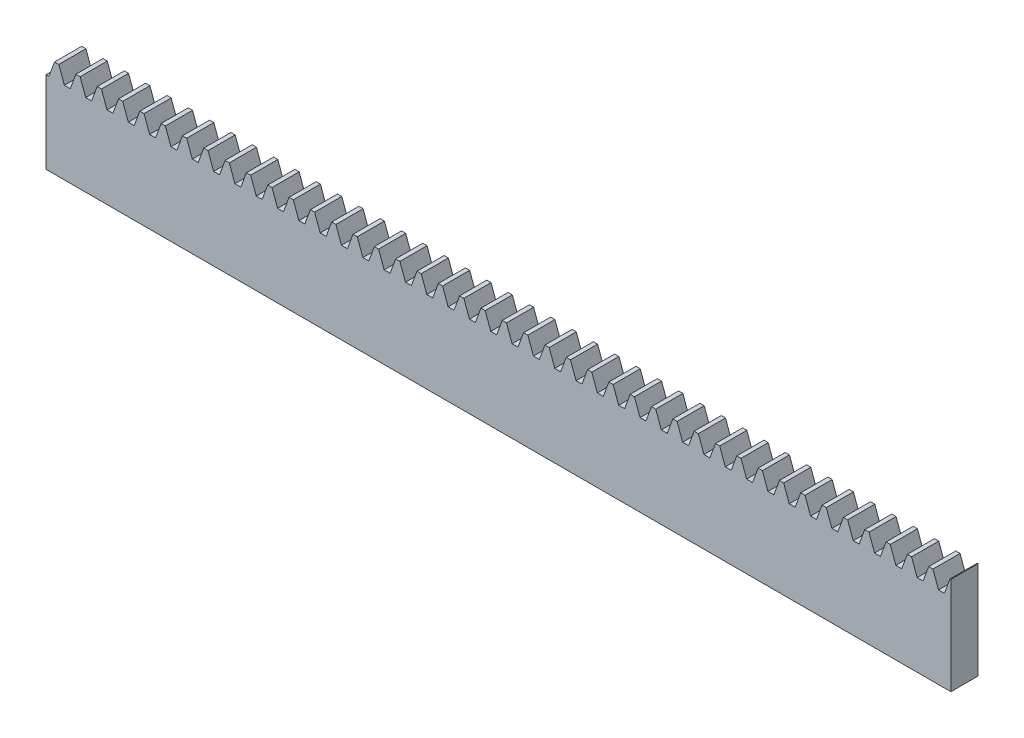
SolidWorks part; units mm, degrees
extrude "Blank" add sketch "BlankSke" against normal blind 12
sketch "BlankSke" plane through (0, 0, 0) normal (0, 0, 1) x (1, 0, 0)
  line L1 (0, 0) -> (400, 0)
  line L2 (0, 0) -> (0, 43)
  line L3 (0, 43) -> (400, 43)
  line L4 (400, 0) -> (400, 43)
  dimension "Length" = 400
  dimension "Blank_height" = 43
ref_plane "Plane1" through (0, 0, 0) normal (0, 0, 1) x (1, 0, 0)
ref_plane "Plane2" through (0, 0, 0) normal (0, 1, 0) x (1, 0, 0)
ref_plane "Plane3" through (0, 0, 0) normal (1, 0, 0) x (0, 0, -1)
sketch "HoldingSke" plane through (0, 0, 0) normal (0, 1, 0) x (1, 0, 0)
  line L0 (0, 0) -> (0.0464, 0.3301)
  line L1 (-15, 0) -> (100, 0) construction
  line L2 (0, 0) -> (-2.1039, 2.3779)
  line L3 (0, 0) -> (-11.863, 4.5341)
  line L4 (0, 0) -> (6.2122, 5.9991)
  line L5 (0, 0) -> (-23.7986, -8.8762)
  line L6 (0, 0) -> (-10.5278, -7.1032)
  line L9 (-71.009, 38.7566) -> (304.8681, 175.5647)
  line L10 (-76.2, 5.3779) -> (-36.2, 5.3779)
  line L11 (0, 0) -> (-12, 0)
  line L12 (-76.2, 101.6) -> (-76.093, 101.6)
  line L13 (24.9733, 27.94) -> (52.9518, 28.4284)
  line L14 (24.9733, 27.94) -> (24.9743, 27.94)
  line L15 (24.9733, 27.94) -> (100.4006, 29.5858)
  circle A0 centre (0, 0) radius 19.05
  circle A1 centre (0, 0) radius 20
  circle A2 centre (0, 0) radius 12.7
  dimension "MPH" = 40
  dimension "Diameter" = 38.1
  dimension "Num_teeth" = 44
  dimension "Pitch" = 0.3333
  dimension "Show_teeth" = 998
  dimension "Thickness" = 12.7
  dimension "Ap" = 20
  dimension "Pitch_height" = 40
  dimension "Width" = 12
  dimension "Backlash" = 0.107
  dimension "Addendum_fac" = 1
  dimension "Dedendum_fac" = 1.25
  dimension "Clearance_fac" = 0.25
  dimension "Dedendum_add" = 0.001
  dimension "Length" = 400
  dimension "Module" = 3
sketch "TooCutSkeIll" plane through (0, 0, 0) normal (0, 0, 1) x (1, 0, 0)
  line L0 (-3.7404, 42.921) -> (-1.4922, 36.7441)
  line L1 (-0.7865, 36.25) -> (0.7865, 36.25)
  line L2 (1.4922, 36.7441) -> (3.7404, 42.921)
  line L3 (400, 43) -> (0, 43) construction
  line L4 (0, 0) -> (0, 64.897) construction
  line L5 (-13.208, 40) -> (12.954, 40) construction
  line L6 (0, 0) -> (400, 0) construction
  line L7 (2.6772, 40) -> (2.6772, 48.7463) construction
  line L8 (-2.6772, 40) -> (-2.6772, 48.7463) construction
  line L9 (3.8531, 43) -> (3.8531, 43.0254)
  line L10 (-3.8531, 43) -> (-3.8531, 43.0254)
  line L11 (-3.8531, 43.0254) -> (3.8531, 43.0254)
  arc A0 (0.7865, 36.25) -> (1.4922, 36.7441) centre (0.7865, 37.001) ccw
  arc A1 (-1.4922, 36.7441) -> (-0.7865, 36.25) centre (-0.7865, 37.001) ccw
  arc A2 (3.8531, 43) -> (3.7404, 42.921) centre (3.8531, 42.88) ccw
  arc A3 (-3.7404, 42.921) -> (-3.8531, 43) centre (-3.8531, 42.88) ccw
  dimension "Pitch_height" = 40
  dimension "Addendum_plus" = 3.0254
  dimension "Pressure_angle" = 20
  dimension "Gap_width" = 5.3544
  dimension "Dedendum" = 3.75
extrude "ToothCutIll" [suppressed] cut sketch "TooCutSkeIll" against normal through all
sketch "TooCutSkeSim" plane through (0, 0, 0) normal (0, 0, 1) x (1, 0, 0)
  line L0 (1.3123, 36.25) -> (-1.3123, 36.25)
  line L1 (3.7784, 43.0254) -> (1.3123, 36.25)
  line L2 (0, 17.4625) -> (0, 53.467) construction
  line L3 (3.7784, 43.0254) -> (-3.7784, 43.0254)
  line L6 (-3.7784, 43.0254) -> (-1.3123, 36.25)
  line L9 (-2.6772, 40) -> (2.6772, 40) construction
  line L10 (0, 0) -> (400, 0) construction
  line L11 (2.6772, 40) -> (2.6772, 53.467) construction
  line L12 (-2.6772, 40) -> (-2.6772, 53.467) construction
  dimension "Pitch_height" = 40
  dimension "Addendum_plus" = 3.0254
  dimension "Pressure_angle" = 20
  dimension "Gap_width" = 5.3544
  dimension "Dedendum" = 3.75
extrude "ToothCutSim" cut sketch "TooCutSkeSim" against normal through all
pattern_linear "TeethCuts" count 43 spacing 9.4248 along (1, 0, 0) of "ToothCutIll", "ToothCutSim"
equation "' \"Module@HoldingSke\" = 6.35"
equation "' \"Num_teeth@HoldingSke\" = 12"
equation "' \"Ap@HoldingSke\" =  20"
equation "' \"Ap@HoldingSke\" = 20"
equation "' \"Width@HoldingSke\" = 0.25 * 25.4"
equation "' \"Show_teeth@HoldingSke\" = 500"
equation "' \"Backlash@HoldingSke\" = 0.009 * 25.4"
equation "' \"Addendum_fac@HoldingSke\" = 1.0"
equation "' \"Dedendum_fac@HoldingSke\" = 1.25"
equation "' \"Dedendum_add@HoldingSke\" = 0.00005 * 25.4"
equation "' \"Clearance_fac@HoldingSke\" = 0.25"
equation "' \"Pitch_height@HoldingSke\" = 1 * 25.4"
equation "' \"Length@HoldingSke\" = 4.71 * 25.4"
equation "\"Pitch@HoldingSke\" = 1 / \"Module@HoldingSke\""
equation "\"MPH@HoldingSke\" = \"Dedendum_fac@HoldingSke\" / \"Pitch@HoldingSke\" + 2 * \"Dedendum_add@HoldingSke\" + 0.002 * 25.4"
equation "\"MPH@HoldingSke\" = ((sgn( \"MPH@HoldingSke\" - \"Pitch_height@HoldingSke\")+1)*( \"MPH@HoldingSke\" - \"Pitch_height@HoldingSke\"))/2 + \"Pitch_height@HoldingSke\""
equation "\"Blank_height@BlankSke\" = \"Pitch_height@HoldingSke\" + \"Addendum_fac@HoldingSke\"  / \"Pitch@HoldingSke\" "
equation "\"Length@BlankSke\" =  \"Length@HoldingSke\""
equation "\"Face_width@Blank\" = \"Width@HoldingSke\""
equation "\"Pressure_angle@TooCutSkeIll\" = \"Ap@HoldingSke\""
equation "\"Addendum_plus@TooCutSkeIll\" =  \"Addendum_fac@HoldingSke\"  / \"Pitch@HoldingSke\" + 0.001 *25.4"
equation "\"Dedendum@TooCutSkeIll\" = \"Dedendum_fac@HoldingSke\"  / \"Pitch@HoldingSke\""
equation "\"Pitch_height@TooCutSkeIll\" =  \"MPH@HoldingSke\""
equation "\"Gap_width@TooCutSkeIll\" = 3.14159265 / 2 / \"Pitch@HoldingSke\" + 6 * \"Backlash@HoldingSke\""
equation "\"Pressure_angle@TooCutSkeSim\" = \"Ap@HoldingSke\""
equation "\"Addendum_plus@TooCutSkeSim\" =  \"Addendum_fac@HoldingSke\"  / \"Pitch@HoldingSke\" + 0.001 * 25.4"
equation "\"Dedendum@TooCutSkeSim\" = \"Dedendum_fac@HoldingSke\"  / \"Pitch@HoldingSke\""
equation "\"Pitch_height@TooCutSkeSim\" =  \"MPH@HoldingSke\""
equation "\"Gap_width@TooCutSkeSim\" = 3.14159265 / 2 / \"Pitch@HoldingSke\" + 6 * \"Backlash@HoldingSke\""
equation "\"Root_fillet@TooCutSkeIll\" = \"Clearance_fac@HoldingSke\" / \"Pitch@HoldingSke\" + \"Dedendum_add@HoldingSke\""
equation "\"Break_rad@TooCutSkeIll\" = 0.02 / \"Pitch@HoldingSke\" * 2"
equation "\"Linear_pitch@TeethCuts\" = 3.14159265 / \"Pitch@HoldingSke\""
equation "\"Num_teeth@HoldingSke\" = int( ( \"Length@HoldingSke\" + 0 ) / (3.14159265 / \"Pitch@HoldingSke\")) + 0.9999  + 1"
equation " \"Num_teeth@TeethCuts\" = int( \"Show_teeth@HoldingSke\" ) + 1"
equation " \"Num_teeth@TeethCuts\" = ((sgn( \"Num_teeth@TeethCuts\" - \"Num_teeth@HoldingSke\" )-1)*( \"Num_teeth@TeethCuts\" - \"Num_teeth@HoldingSke\" ))/-2+ \"Num_teeth@HoldingSke\""
equation " \"Num_teeth@TeethCuts\" = ((sgn( \"Num_teeth@TeethCuts\" - 2.0)+1)*( \"Num_teeth@TeethCuts\" - 2.0))/2 +2.0"
